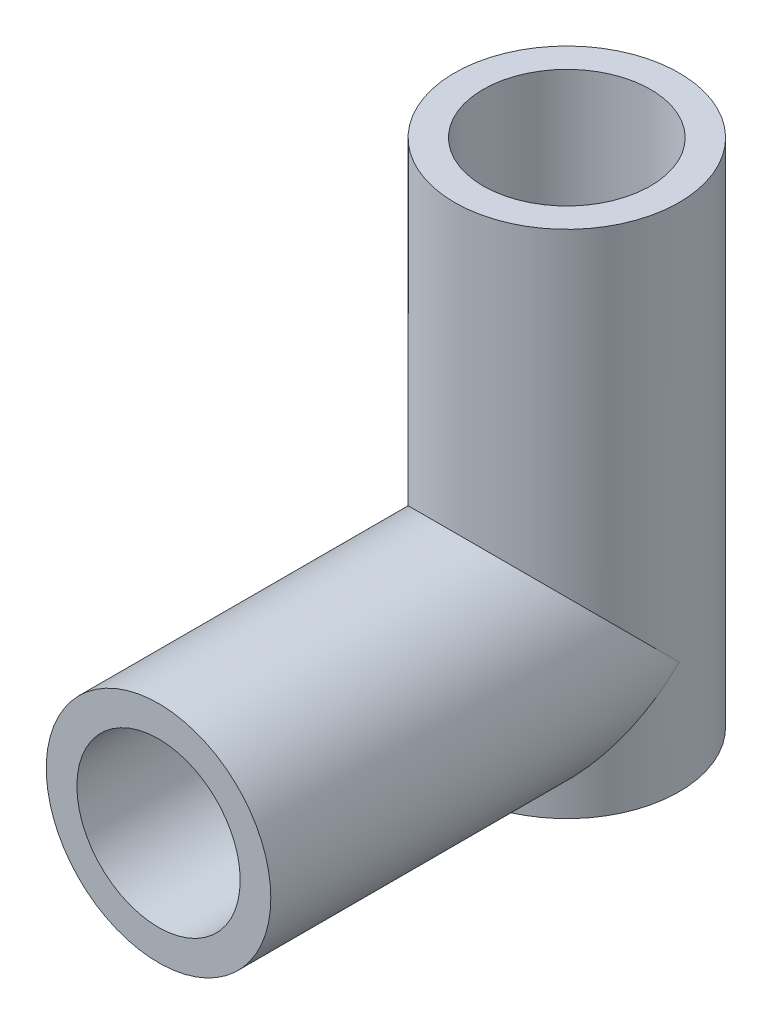
SolidWorks part; units mm, degrees
ref_plane "前视基准面" through (0, 0, 0) normal (0, 0, 1) x (1, 0, 0)
ref_plane "上视基准面" through (0, 0, 0) normal (0, 1, 0) x (1, 0, 0)
ref_plane "右视基准面" through (0, 0, 0) normal (1, 0, 0) x (0, 0, -1)
other "Configuration Table"
sketch "草图1" plane through (0, 0, 0) normal (0, 1, 0) x (1, 0, 0)
  circle A0 centre (0, 0) radius 4.1
  circle A1 centre (0, 0) radius 5.5
  dimension "D1" = 8.2
  dimension "D2" = 11
extrude "凸台-拉伸1" add sketch "草图1" along normal blind 25
sketch "草图2" plane through (0, 0, 0) normal (0, 0, 1) x (1, 0, 0)
  line L0 (-5.5, 0) -> (5.5, 0) construction
  circle A0 centre (0, 5.5) radius 4
  circle A1 centre (0, 5.5) radius 5.5
  dimension "D1" = 8
  dimension "D2" = 11
extrude "凸台-拉伸2" add sketch "草图2" along normal blind 20
sketch "草图4" plane through (0, 0, 0) normal (0, 1, 0) x (1, 0, 0)
  circle A0 centre (0, 0) radius 4.1
extrude "切除-拉伸1" cut sketch "草图4" along normal blind 20
sketch "草图5" plane through (0, 0, 20) normal (0, 0, 1) x (1, 0, 0)
  circle A0 centre (0, 5.5) radius 4
extrude "切除-拉伸2" cut sketch "草图5" against normal blind 20
